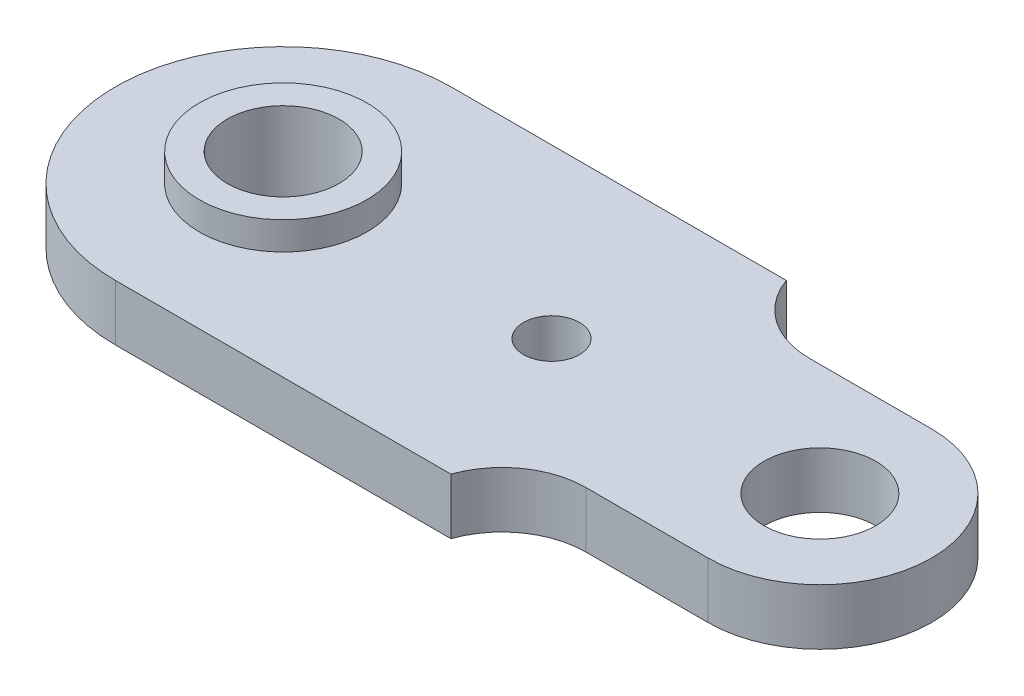
SolidWorks part; units mm, degrees
ref_plane "Front Plane" through (0, 0, 0) normal (0, 0, 1) x (1, 0, 0)
ref_plane "Top Plane" through (0, 0, 0) normal (0, 1, 0) x (1, 0, 0)
ref_plane "Right Plane" through (0, 0, 0) normal (1, 0, 0) x (0, 0, -1)
sketch "Sketch1" plane through (0, 0, 0) normal (0, 1, 0) x (1, 0, 0)
  line L0 (0, -30) -> (60, -30)
  line L1 (0, 30) -> (60, 30)
  line L2 (60, -46.4949) -> (60, 97.318) construction
  line L3 (135.5379, 20) -> (-149.7951, 20) construction
  line L4 (140.4737, 0) -> (-102.8235, 0) construction
  line L5 (146.0893, -20) -> (-24.9754, -20) construction
  line L6 (74.1421, -20) -> (96, -20)
  line L7 (96, 20) -> (74.1421, 20)
  circle A0 centre (0, 0) radius 30
  circle A1 centre (96, 0) radius 20
  circle A5 centre (74.1421, 35) radius 15
  circle A6 centre (74.1421, -35) radius 15
  dimension "D1" = 60
  dimension "D2" = 40
  dimension "D3" = 15
  dimension "D4" = 30
  dimension "D5" = 15
  dimension "D10" = 30
  dimension "D6" = 60
  dimension "D8" = 96
  dimension "D9" = 60
extrude "Boss-Extrude1" add sketch "Sketch1" along normal blind 10 contours A0 | A6 L6 A1 L7 A5 L1 A0 L0 | A1 L1
sketch "Sketch2" plane through (0, 10, 0) normal (0, 1, 0) x (1, 0, 0)
  circle A0 centre (0, 0) radius 15
  dimension "D1" = 30
extrude "Boss-Extrude2" add sketch "Sketch2" along normal blind 5
sketch "Sketch3" plane through (0, 15, 0) normal (0, 1, 0) x (1, 0, 0)
  circle A0 centre (0, 0) radius 10
  dimension "D1" = 20
extrude "Cut-Extrude1" cut sketch "Sketch3" against normal through all
sketch "Sketch4" plane through (0, 10, 0) normal (0, 1, 0) x (1, 0, 0)
  circle A0 centre (48, 0) radius 5
  dimension "D1" = 10
  dimension "D2" = 48
  dimension "D3" = 48
extrude "Cut-Extrude2" cut sketch "Sketch4" against normal through all
sketch "Sketch5" plane through (0, 10, 0) normal (0, 1, 0) x (1, 0, 0)
  circle A0 centre (96, 0) radius 10
  dimension "D1" = 20
extrude "Cut-Extrude3" cut sketch "Sketch5" against normal through all
